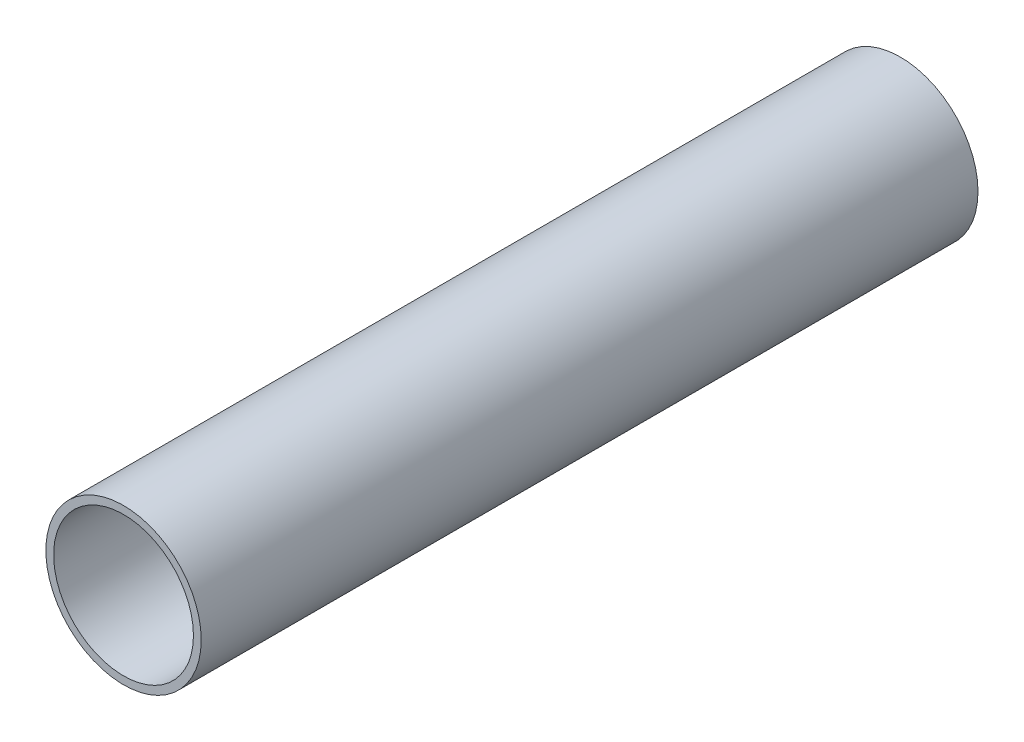
SolidWorks part; units mm, degrees
material "Carbon Fiber Tube - UD Approx"
ref_plane "Front Plane" through (0, 0, 0) normal (0, 0, 1) x (1, 0, 0)
ref_plane "Top Plane" through (0, 0, 0) normal (0, 1, 0) x (1, 0, 0)
ref_plane "Right Plane" through (0, 0, 0) normal (1, 0, 0) x (0, 0, -1)
sketch "Sketch1" plane through (0, 0, 0) normal (0, 0, 1) x (1, 0, 0)
  circle A0 centre (0, 0) radius 10
  circle A1 centre (0, 0) radius 9
  dimension "D1" = 20
  dimension "D2" = 18
extrude "Boss-Extrude1" add sketch "Sketch1" along normal blind 100
